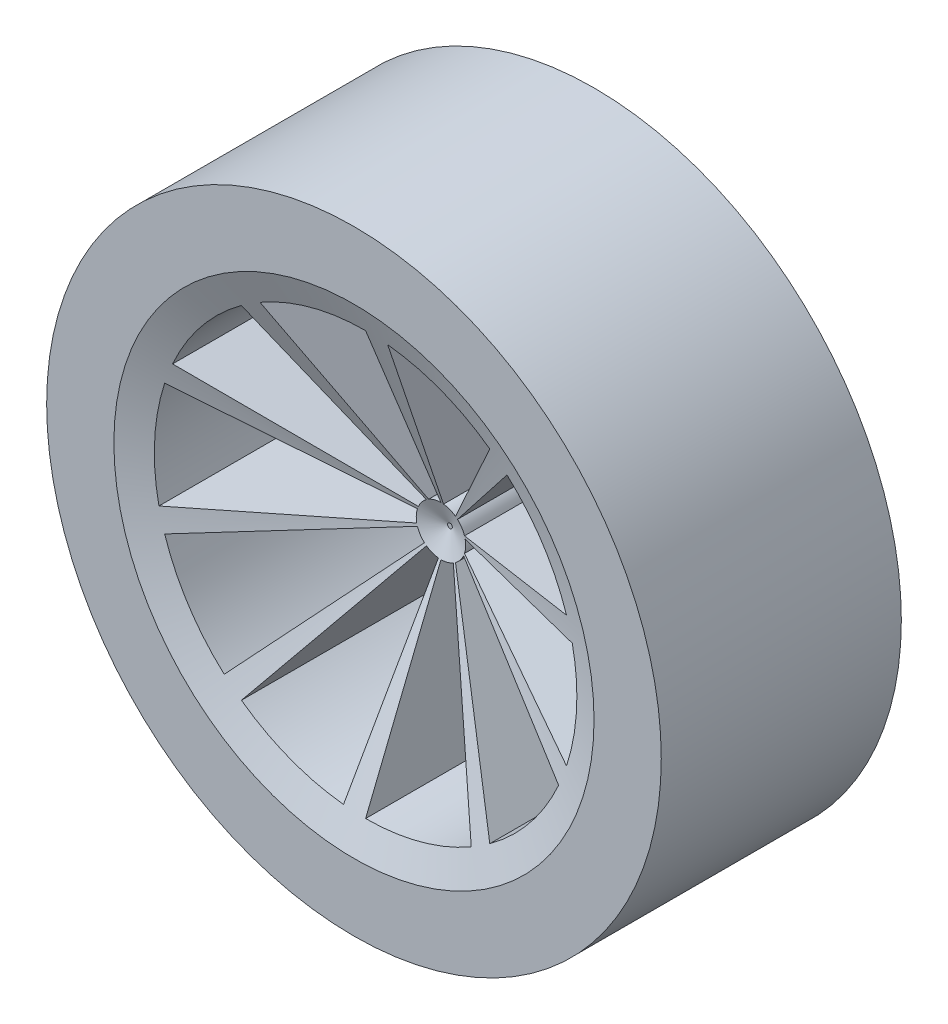
SolidWorks part; units mm, degrees
ref_plane "정면" through (0, 0, 0) normal (0, 0, 1) x (1, 0, 0)
ref_plane "윗면" through (0, 0, 0) normal (0, 1, 0) x (1, 0, 0)
ref_plane "우측면" through (0, 0, 0) normal (1, 0, 0) x (0, 0, -1)
sketch "스케치1" plane through (0, 0, 0) normal (0, 0, 1) x (1, 0, 0)
  circle A0 centre (0, 0) radius 32
  dimension "D1" = 64
extrude "보스-돌출1" add sketch "스케치1" along normal blind 25
sketch "스케치2" plane through (0, 0, 25) normal (0, 0, 1) x (1, 0, 0)
  circle A0 centre (0, 0) radius 25
  dimension "D1" = 50
extrude "컷-돌출1" cut sketch "스케치2" against normal blind 10 draft 68
sketch "스케치3" plane through (0, 0, 25) normal (0, 0, 1) x (1, 0, 0)
  point P24 (0, 0)
sketch "스케치4" plane through (0, 0, 0) normal (0, 0, -1) x (-1, 0, 0)
  line L0 (0, 22) -> (0, 2.5751)
  line L1 (11, 19.0526) -> (1.2876, 2.2301)
  line L2 (20.098, 8.9482) -> (2.3525, 1.0474)
  line L3 (12.9313, 17.7984) -> (1.5136, 2.0833)
  line L4 (21.5192, -4.5741) -> (2.5189, -0.5354)
  line L5 (20.9232, 6.7984) -> (2.4491, 0.7958)
  line L6 (14.7209, -16.3492) -> (1.7231, -1.9137)
  line L7 (20.9232, -6.7984) -> (2.4491, -0.7958)
  line L8 (2.2996, -21.8795) -> (0.2692, -2.561)
  line L9 (12.9313, -17.7984) -> (1.5136, -2.0833)
  line L10 (-11, -19.0526) -> (-1.2876, -2.2301)
  line L11 (0, -22) -> (0, -2.5751)
  line L12 (-20.098, -8.9482) -> (-2.3525, -1.0474)
  line L13 (-12.9313, -17.7984) -> (-1.5136, -2.0833)
  line L14 (-21.5192, 4.5741) -> (-2.5189, 0.5354)
  line L15 (-20.9232, -6.7984) -> (-2.4491, -0.7958)
  line L16 (-14.7209, 16.3492) -> (-1.7231, 1.9137)
  line L17 (-20.9232, 6.7984) -> (-2.4491, 0.7958)
  line L18 (-2.2996, 21.8795) -> (-0.2692, 2.561)
  line L19 (-12.9313, 17.7984) -> (-1.5136, 2.0833)
  arc A1 (0, 22) -> (11, 19.0526) centre (0, 0) cw
  arc A2 (0, 2.5751) -> (1.2876, 2.2301) centre (0, 0) cw
  arc A3 (1.5136, 2.0833) -> (2.3525, 1.0474) centre (0, 0) cw
  arc A4 (12.9313, 17.7984) -> (20.098, 8.9482) centre (0, 0) cw
  arc A5 (2.4491, 0.7958) -> (2.5189, -0.5354) centre (0, 0) cw
  arc A6 (20.9232, 6.7984) -> (21.5192, -4.5741) centre (0, 0) cw
  arc A7 (2.4491, -0.7958) -> (1.7231, -1.9137) centre (0, 0) cw
  arc A8 (20.9232, -6.7984) -> (14.7209, -16.3492) centre (0, 0) cw
  arc A9 (1.5136, -2.0833) -> (0.2692, -2.561) centre (0, 0) cw
  arc A10 (12.9313, -17.7984) -> (2.2996, -21.8795) centre (0, 0) cw
  arc A11 (0, -2.5751) -> (-1.2876, -2.2301) centre (0, 0) cw
  arc A12 (0, -22) -> (-11, -19.0526) centre (0, 0) cw
  arc A13 (-1.5136, -2.0833) -> (-2.3525, -1.0474) centre (0, 0) cw
  arc A14 (-12.9313, -17.7984) -> (-20.098, -8.9482) centre (0, 0) cw
  arc A15 (-2.4491, -0.7958) -> (-2.5189, 0.5354) centre (0, 0) cw
  arc A16 (-20.9232, -6.7984) -> (-21.5192, 4.5741) centre (0, 0) cw
  arc A17 (-2.4491, 0.7958) -> (-1.7231, 1.9137) centre (0, 0) cw
  arc A18 (-20.9232, 6.7984) -> (-14.7209, 16.3492) centre (0, 0) cw
  arc A19 (-1.5136, 2.0833) -> (-0.2692, 2.561) centre (0, 0) cw
  arc A20 (-12.9313, 17.7984) -> (-2.2996, 21.8795) centre (0, 0) cw
  point P45 (0, 0)
  dimension "D1" = 10
extrude "컷-돌출6" cut sketch "스케치4" against normal blind 50
